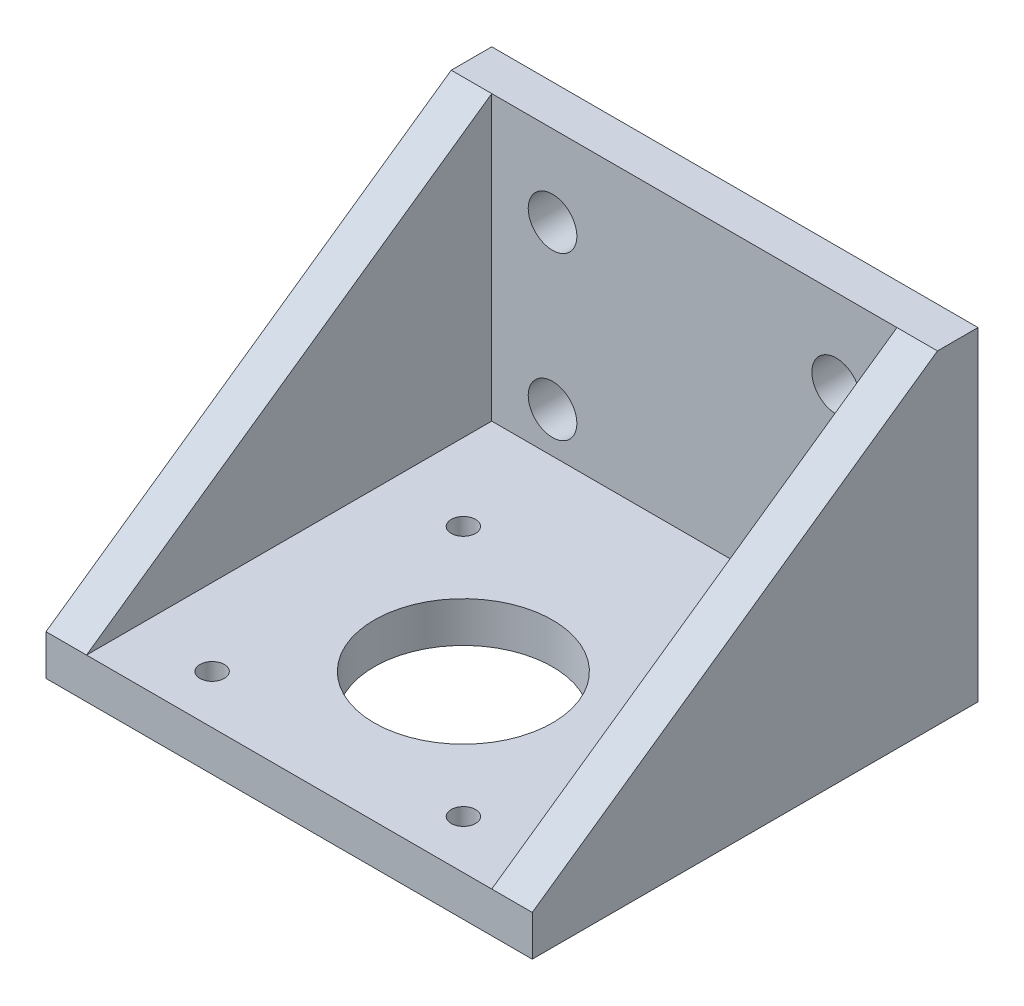
SolidWorks part; units mm, degrees
ref_plane "Спереди" through (0, 0, 0) normal (0, 0, 1) x (1, 0, 0)
ref_plane "Сверху" through (0, 0, 0) normal (0, 1, 0) x (1, 0, 0)
ref_plane "Справа" through (0, 0, 0) normal (1, 0, 0) x (0, 0, -1)
sketch "Эскиз1" plane through (0, 0, 0) normal (0, 1, 0) x (1, 0, 0)
  line L0 (30, 55) -> (30, 0) construction
  line L1 (0, 0) -> (60, 0)
  line L2 (0, 0) -> (0, 55)
  line L3 (0, 55) -> (60, 55)
  line L4 (60, 0) -> (60, 55)
  line L5 (19, 21.5) -> (41, 21.5) construction
  circle A0 centre (30, 21.5) radius 11
  circle A1 centre (14.5, 37) radius 1.5
  circle A2 centre (45.5, 37) radius 1.5
  circle A3 centre (45.5, 6) radius 1.5
  circle A4 centre (14.5, 6) radius 1.5
  dimension "D5" = 3
  dimension "D7" = 22
  dimension "D1" = 55
  dimension "D2" = 60
  dimension "D3" = 31
  dimension "D4" = 31
  dimension "D6" = 21.5
extrude "Бобышка-Вытянуть1" add sketch "Эскиз1" along normal blind 5
sketch "Эскиз3" plane through (0, 5, 0) normal (0, 1, 0) x (1, 0, 0)
  line L0 (5, 50) -> (55, 50)
  line L1 (55, 50) -> (55, 0)
  line L2 (0, 0) -> (60, 0) construction
  line L3 (55, 0) -> (60, 0)
  line L4 (60, 0) -> (60, 55)
  line L5 (60, 55) -> (0, 55)
  line L6 (0, 55) -> (0, 0)
  line L7 (0, 0) -> (5, 0)
  line L8 (5, 0) -> (5, 50)
  dimension "D1" = 5
  dimension "D2" = 5
  dimension "D3" = 5
  dimension "D4" = 50
extrude "Бобышка-Вытянуть2" add sketch "Эскиз3" along normal blind 35
sketch "Эскиз4" plane through (0, 0, -55) normal (0, 0, -1) x (-1, 0, 0)
  line L0 (-30, 0) -> (-30, 40) construction
  line L1 (-60, 0) -> (0, 0) construction
  line L2 (-60, 40) -> (0, 40) construction
  line L3 (0, 10) -> (-60, 10) construction
  line L4 (0, 40) -> (0, 0) construction
  line L5 (-60, 40) -> (-60, 0) construction
  line L6 (-60, 30) -> (0, 30) construction
  circle A0 centre (-12.5, 10) radius 3
  circle A1 centre (-12.5, 30) radius 3
  circle A2 centre (-47.5, 30) radius 3
  circle A3 centre (-47.5, 10) radius 3
  dimension "D3" = 6
  dimension "D1" = 10
  dimension "D2" = 10
  dimension "D4" = 35
  dimension "D5" = 35
extrude "Вырез-Вытянуть1" cut sketch "Эскиз4" against normal up to surface (5 mm away) up to face at (30, 22.5, -50)
sketch "Эскиз5" plane through (0, 0, 0) normal (-1, 0, 0) x (0, 0, 1)
  line L0 (0, 5) -> (-50, 40)
  line L1 (0, 40) -> (0, 0) construction
  line L2 (-55, 40) -> (0, 40) construction
  line L3 (-50, 40) -> (0, 40)
  line L4 (0, 40) -> (0, 5)
  line L5 (-55, 0) -> (0, 0) construction
  line L6 (-55, 40) -> (-55, 0) construction
  dimension "D1" = 5
  dimension "D2" = 5
extrude "Вырез-Вытянуть2" cut sketch "Эскиз5" against normal up to surface (60 mm away) up to face at (60, 20, -27.5)
